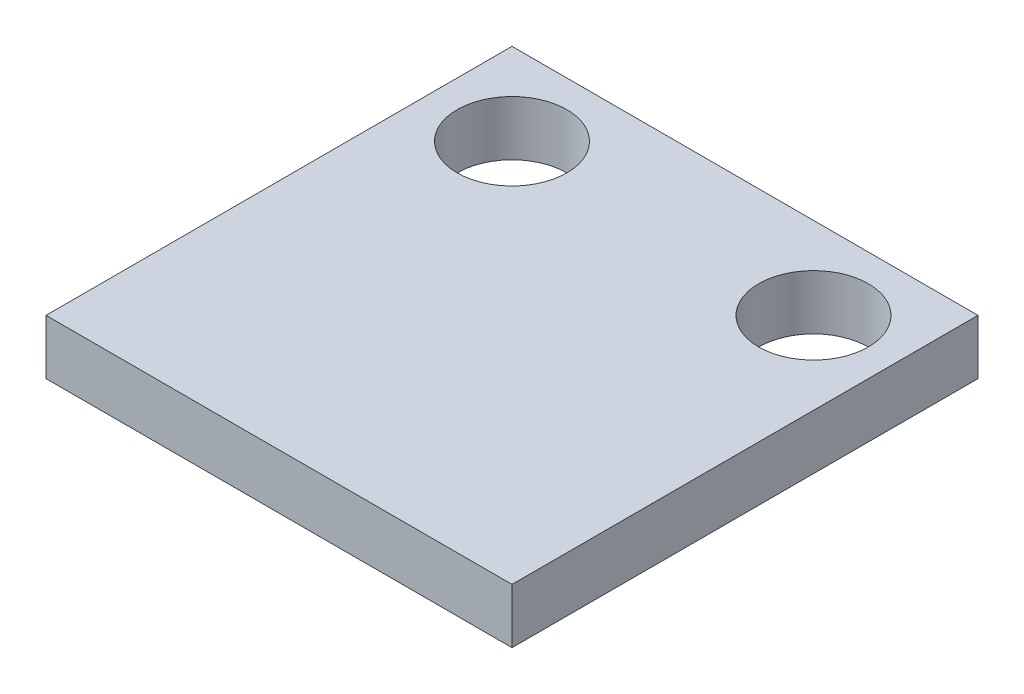
SolidWorks part; units mm, degrees
material "ABS"
ref_plane "Front Plane" through (0, 0, 0) normal (0, 0, 1) x (1, 0, 0)
ref_plane "Top Plane" through (0, 0, 0) normal (0, 1, 0) x (1, 0, 0)
ref_plane "Right Plane" through (0, 0, 0) normal (1, 0, 0) x (0, 0, -1)
sketch "Sketch1" plane through (0, 0, 0) normal (0, 1, 0) x (1, 0, 0)
  line L1 (0, 0) -> (17, 0)
  line L2 (0, 0) -> (0, 17)
  line L3 (0, 17) -> (17, 17)
  line L4 (17, 0) -> (17, 17)
  circle A0 centre (3, 14) radius 2
  circle A1 centre (14, 14) radius 2
  dimension "D5" = 4
  dimension "D1" = 17
  dimension "D2" = 17
  dimension "D3" = 3
  dimension "D4" = 3
  dimension "D6" = 3
extrude "Boss-Extrude1" add sketch "Sketch1" along normal blind 2
